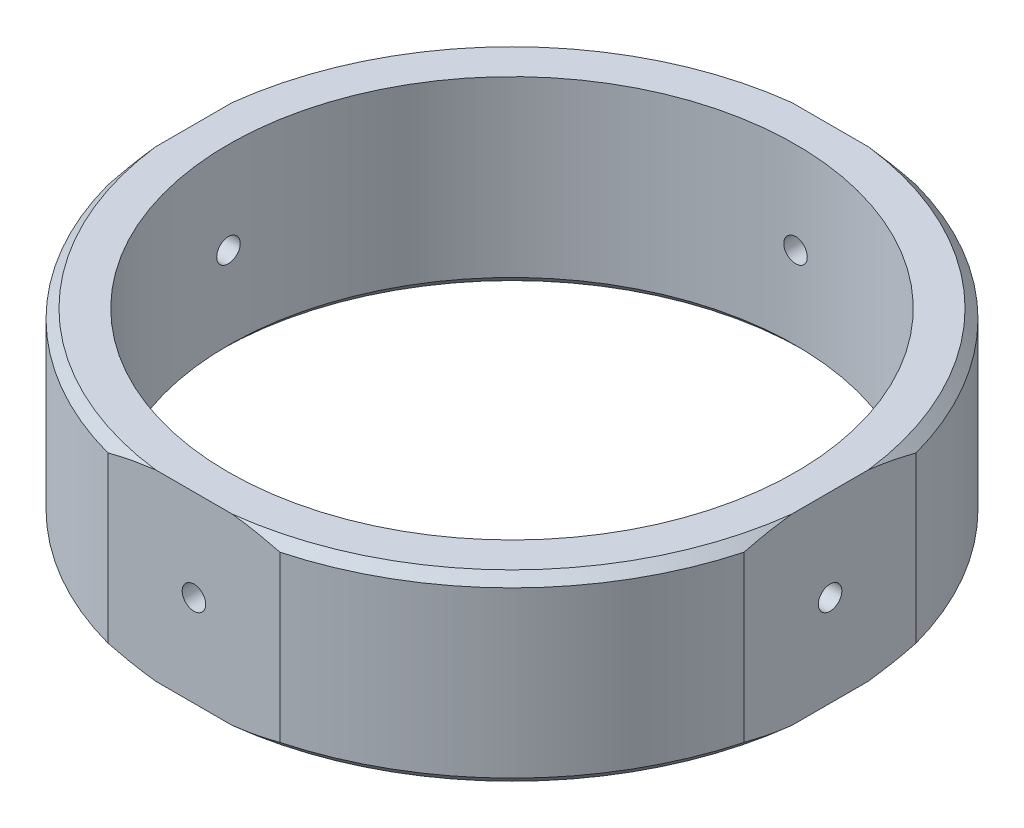
SolidWorks part; units mm, degrees
ref_plane "Front Plane" through (0, 0, 0) normal (0, 0, 1) x (1, 0, 0)
ref_plane "Top Plane" through (0, 0, 0) normal (0, 1, 0) x (1, 0, 0)
ref_plane "Right Plane" through (0, 0, 0) normal (1, 0, 0) x (0, 0, -1)
sketch "Sketch1" plane through (0, 0, 0) normal (0, 1, 0) x (1, 0, 0)
  circle A0 centre (0, 0) radius 78.74
  circle A1 centre (0, 0) radius 91.44
  dimension "D1" = 157.48
  dimension "D2" = 12.7
extrude "Boss-Extrude1" add sketch "Sketch1" along normal blind 50.8
chamfer "Chamfer1" distance 2.54 angle 45 3 edges at (0, 50.8, 91.44) (0, 0, 91.44) (0, 0, 78.74)
sketch "Sketch2" plane through (0, 0, 0) normal (0, 0, 1) x (1, 0, 0)
  line L0 (91.44, 2.54) -> (91.44, 48.26) construction
  line L1 (88.265, 69.3537) -> (104.5232, 69.3537)
  line L2 (88.265, 69.3537) -> (88.265, -18.1756)
  line L3 (88.265, -18.1756) -> (104.5232, -18.1756)
  line L4 (104.5232, 69.3537) -> (104.5232, -18.1756)
  dimension "D1" = 3.175
extrude "Cut-Extrude1" cut sketch "Sketch2" against normal mid plane 254 contours L4 L3 L2 L1
pattern_circular "CirPattern1" count 4 over 360 about axis through (0, 0, 0) along (0, 1, 0) of "Cut-Extrude1"
sketch "Sketch3" plane through (0, 0, -88.265) normal (0, 0, -1) x (-1, 0, 0)
  line L0 (10.6066, 50.8) -> (-10.6066, 50.8) construction
  line L1 (23.8865, 48.26) -> (23.8865, 2.54) construction
  circle A0 centre (0, 25.4) radius 3.2639
  point P6 (0, 0)
  point P9 (0, 0)
  point P10 (0, 0)
  dimension "D1" = 25.4
  dimension "D2" = 23.8865
extrude "Cut-Extrude2" cut sketch "Sketch3" against normal through all
pattern_circular "CirPattern2" count 4 over 360 about axis through (0, 50.8, 0) along (0, 1, 0) of "Cut-Extrude2"
equation "\"shoulder offset\"=0.5"
equation "\"ID\"=6.17"
equation "\"L\"= 2"
equation "\"D1@Sketch1\"=\"ID\"+\"ID offset\""
equation "\"D2@Sketch1\"=\"shoulder offset\""
equation "\"D1@Boss-Extrude1\"=\"L\""
equation "\"ID offset\" = .03"
